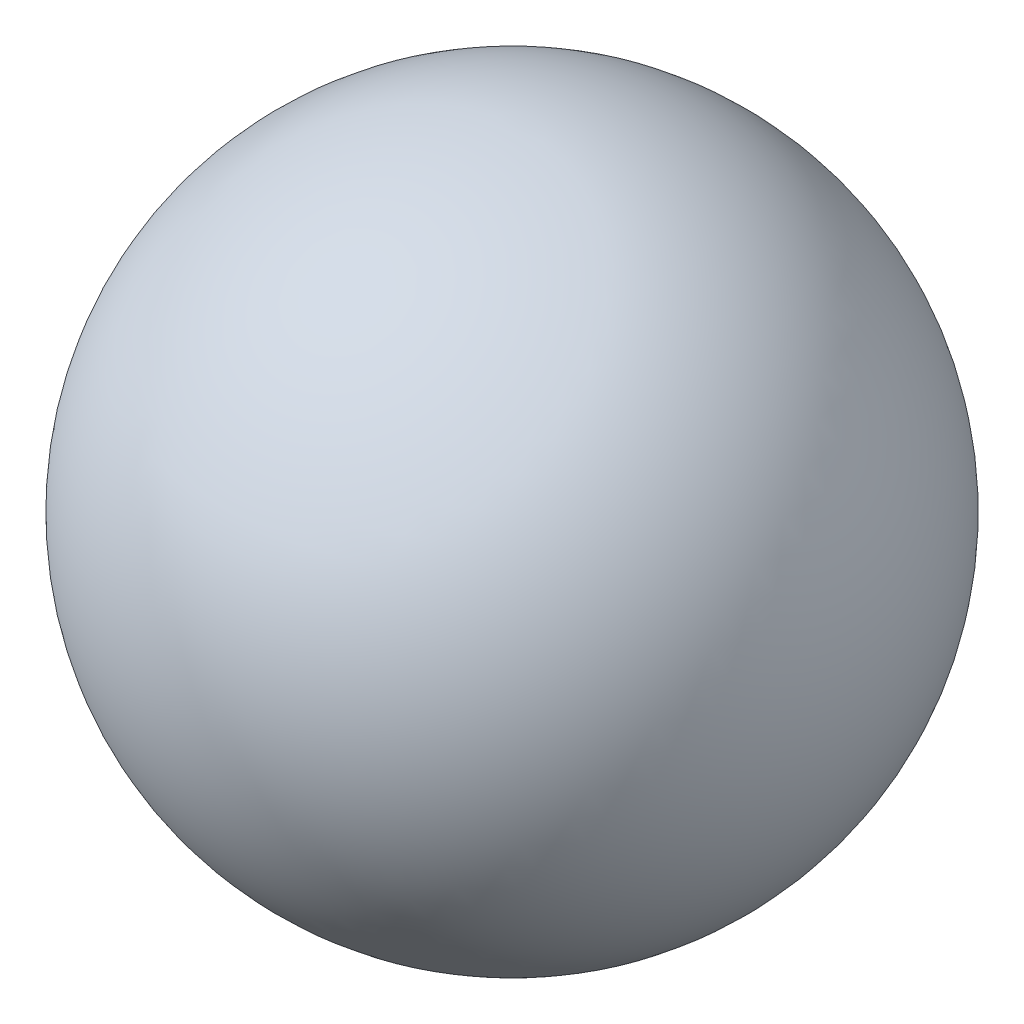
SolidWorks part; units mm, degrees
ref_plane "Plan de face" through (0, 0, 0) normal (0, 0, 1) x (1, 0, 0)
ref_plane "Plan de dessus" through (0, 0, 0) normal (0, 1, 0) x (1, 0, 0)
ref_plane "Plan de droite" through (0, 0, 0) normal (1, 0, 0) x (0, 0, -1)
sketch "Sketch1" plane through (0, 0, 0) normal (0, 0, 1) x (1, 0, 0)
  line L0 (0, 30) -> (0, -30)
  arc A0 (0, -30) -> (0, 30) centre (0, 0) ccw
  dimension "D1" = 60
revolve "Revolve1" add sketch "Sketch1" angle 360 about L0
